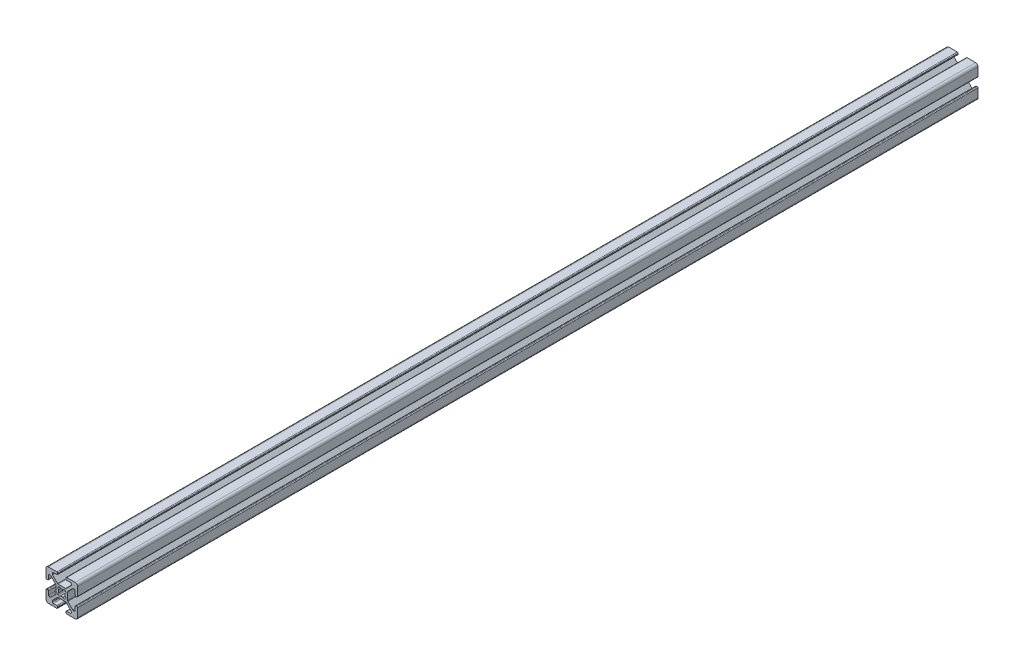
SolidWorks part; units mm, degrees
ref_plane "Front Plane" through (0, 0, 0) normal (0, 0, 1) x (1, 0, 0)
ref_plane "Top Plane" through (0, 0, 0) normal (0, 1, 0) x (1, 0, 0)
ref_plane "Right Plane" through (0, 0, 0) normal (1, 0, 0) x (0, 0, -1)
sketch "Sketch1" plane through (0, 0, 0) normal (0, 0, 1) x (1, 0, 0)
  line L0 (-5.0323, -0.3411) -> (-5.5163, -0.3411)
  line L1 (-6.0243, 0.1669) -> (-6.0243, 2.5159)
  line L2 (-4.5243, 0.1669) -> (-4.5243, 5.5289)
  line L3 (-10.8693, -5.355) -> (-10.8693, -0.5871)
  line L4 (-7.2582, 3.0239) -> (-6.5323, 3.0239)
  line L5 (-7.6174, 2.8752) -> (-10.7205, -0.2279)
  line L6 (-5.0323, -5.6011) -> (-5.5163, -5.6011)
  line L7 (-4.5243, -6.1091) -> (-4.5243, -11.4711)
  line L8 (-6.0243, -6.1091) -> (-6.0243, -8.4581)
  line L9 (-7.2582, -8.9661) -> (-6.5323, -8.9661)
  line L10 (-7.6174, -8.8173) -> (-10.7205, -5.7142)
  line L11 (-12.3994, -5.2756) -> (-12.2198, -5.096)
  line L12 (-17.1543, 6.5209) -> (-17.1543, 6.0369)
  line L13 (-17.6623, 7.0289) -> (-23.0243, 7.0289)
  line L14 (-17.6623, 5.5289) -> (-20.0113, 5.5289)
  line L15 (-12.1404, 0.6839) -> (-16.9082, 0.6839)
  line L16 (-20.5193, 4.295) -> (-20.5193, 5.0209)
  line L17 (-20.3705, 3.9358) -> (-17.2674, 0.8327)
  line L18 (-11.8943, 6.5209) -> (-11.8943, 6.0369)
  line L19 (-11.3863, 7.0289) -> (-6.0243, 7.0289)
  line L20 (-11.3863, 5.5289) -> (-9.0373, 5.5289)
  line L21 (-8.5293, 4.295) -> (-8.5293, 5.0209)
  line L22 (-8.6781, 3.9358) -> (-11.7812, 0.8327)
  line L23 (-12.2198, -0.8462) -> (-12.3994, -0.6666)
  line L24 (-24.0163, -5.6011) -> (-23.5323, -5.6011)
  line L25 (-24.5243, -6.1091) -> (-24.5243, -11.4711)
  line L26 (-23.0243, -6.1091) -> (-23.0243, -8.4581)
  line L27 (-18.1793, -0.5871) -> (-18.1793, -5.355)
  line L28 (-21.7904, -8.9661) -> (-22.5163, -8.9661)
  line L29 (-21.4312, -8.8173) -> (-18.3281, -5.7142)
  line L30 (-24.0163, -0.3411) -> (-23.5323, -0.3411)
  line L31 (-24.5243, 0.1669) -> (-24.5243, 5.5289)
  line L32 (-23.0243, 0.1669) -> (-23.0243, 2.5159)
  line L33 (-21.7904, 3.0239) -> (-22.5163, 3.0239)
  line L34 (-21.4312, 2.8752) -> (-18.3281, -0.2279)
  line L35 (-16.6492, -0.6666) -> (-16.8288, -0.8462)
  line L36 (-11.8943, -12.4631) -> (-11.8943, -11.9791)
  line L37 (-11.3863, -12.9711) -> (-6.0243, -12.9711)
  line L38 (-11.3863, -11.4711) -> (-9.0373, -11.4711)
  line L39 (-16.9082, -6.6261) -> (-12.1404, -6.6261)
  line L40 (-8.5293, -10.2371) -> (-8.5293, -10.9631)
  line L41 (-8.6781, -9.8779) -> (-11.7812, -6.7748)
  line L42 (-17.1543, -12.4631) -> (-17.1543, -11.9791)
  line L43 (-17.6623, -12.9711) -> (-23.0243, -12.9711)
  line L44 (-17.6623, -11.4711) -> (-20.0113, -11.4711)
  line L45 (-20.5193, -10.2371) -> (-20.5193, -10.9631)
  line L46 (-20.3705, -9.8779) -> (-17.2674, -6.7748)
  line L47 (-16.8288, -5.096) -> (-16.6492, -5.2756)
  arc A0 (-15.3283, -4.9062) -> (-13.7203, -4.9062) centre (-14.5243, -2.9711) ccw
  arc A1 (-6.0243, 2.5159) -> (-6.5323, 3.0239) centre (-6.5323, 2.5159) ccw
  arc A2 (-7.2582, 3.0239) -> (-7.6174, 2.8752) centre (-7.2582, 2.5159) ccw
  arc A3 (-10.7205, -0.2279) -> (-10.8693, -0.5871) centre (-10.3613, -0.5871) ccw
  arc A4 (-10.8693, -5.355) -> (-10.7205, -5.7142) centre (-10.3613, -5.355) ccw
  arc A5 (-7.6174, -8.8173) -> (-7.2582, -8.9661) centre (-7.2582, -8.4581) ccw
  arc A6 (-6.5323, -8.9661) -> (-6.0243, -8.4581) centre (-6.5323, -8.4581) ccw
  arc A7 (-5.5163, -5.6011) -> (-6.0243, -6.1091) centre (-5.5163, -6.1091) ccw
  arc A8 (-4.5243, -6.1091) -> (-5.0323, -5.6011) centre (-5.0323, -6.1091) ccw
  arc A9 (-5.0323, -0.3411) -> (-4.5243, 0.1669) centre (-5.0323, 0.1669) ccw
  arc A10 (-6.0243, 0.1669) -> (-5.5163, -0.3411) centre (-5.5163, 0.1669) ccw
  arc A11 (-13.7203, -4.9062) -> (-12.3994, -5.2756) centre (-12.9559, -4.7191) ccw
  arc A12 (-12.2198, -5.096) -> (-12.5892, -3.775) centre (-12.7763, -4.5395) ccw
  arc A13 (-17.1543, 6.5209) -> (-17.6623, 7.0289) centre (-17.6623, 6.5209) ccw
  arc A14 (-17.6623, 5.5289) -> (-17.1543, 6.0369) centre (-17.6623, 6.0369) ccw
  arc A15 (-12.5892, -3.775) -> (-12.5892, -2.1671) centre (-14.5243, -2.9711) ccw
  arc A16 (-17.2674, 0.8327) -> (-16.9082, 0.6839) centre (-16.9082, 1.1919) ccw
  arc A17 (-20.0113, 5.5289) -> (-20.5193, 5.0209) centre (-20.0113, 5.0209) ccw
  arc A18 (-20.5193, 4.295) -> (-20.3705, 3.9358) centre (-20.0113, 4.295) ccw
  arc A19 (-11.8943, 6.0369) -> (-11.3863, 5.5289) centre (-11.3863, 6.0369) ccw
  arc A20 (-11.3863, 7.0289) -> (-11.8943, 6.5209) centre (-11.3863, 6.5209) ccw
  arc A21 (-8.5293, 5.0209) -> (-9.0373, 5.5289) centre (-9.0373, 5.0209) ccw
  arc A22 (-8.6781, 3.9358) -> (-8.5293, 4.295) centre (-9.0373, 4.295) ccw
  arc A23 (-12.1404, 0.6839) -> (-11.7812, 0.8327) centre (-12.1404, 1.1919) ccw
  arc A24 (-12.5892, -2.1671) -> (-12.2198, -0.8462) centre (-12.7763, -1.4027) ccw
  arc A25 (-12.3994, -0.6666) -> (-13.7203, -1.0359) centre (-12.9559, -1.223) ccw
  arc A26 (-24.0163, -5.6011) -> (-24.5243, -6.1091) centre (-24.0163, -6.1091) ccw
  arc A27 (-23.0243, -6.1091) -> (-23.5323, -5.6011) centre (-23.5323, -6.1091) ccw
  arc A28 (-13.7203, -1.0359) -> (-15.3283, -1.0359) centre (-14.5243, -2.9711) ccw
  arc A29 (-18.3281, -5.7142) -> (-18.1793, -5.355) centre (-18.6873, -5.355) ccw
  arc A30 (-23.0243, -8.4581) -> (-22.5163, -8.9661) centre (-22.5163, -8.4581) ccw
  arc A31 (-21.7904, -8.9661) -> (-21.4312, -8.8173) centre (-21.7904, -8.4581) ccw
  arc A32 (-23.5323, -0.3411) -> (-23.0243, 0.1669) centre (-23.5323, 0.1669) ccw
  arc A33 (-24.5243, 0.1669) -> (-24.0163, -0.3411) centre (-24.0163, 0.1669) ccw
  arc A34 (-22.5163, 3.0239) -> (-23.0243, 2.5159) centre (-22.5163, 2.5159) ccw
  arc A35 (-21.4312, 2.8752) -> (-21.7904, 3.0239) centre (-21.7904, 2.5159) ccw
  arc A36 (-18.1793, -0.5871) -> (-18.3281, -0.2279) centre (-18.6873, -0.5871) ccw
  arc A37 (-15.3283, -1.0359) -> (-16.6492, -0.6666) centre (-16.0927, -1.223) ccw
  arc A38 (-16.8288, -0.8462) -> (-16.4594, -2.1671) centre (-16.2723, -1.4027) ccw
  arc A39 (-11.8943, -12.4631) -> (-11.3863, -12.9711) centre (-11.3863, -12.4631) ccw
  arc A40 (-11.3863, -11.4711) -> (-11.8943, -11.9791) centre (-11.3863, -11.9791) ccw
  arc A41 (-16.4594, -2.1671) -> (-16.4594, -3.775) centre (-14.5243, -2.9711) ccw
  arc A42 (-11.7812, -6.7748) -> (-12.1404, -6.6261) centre (-12.1404, -7.1341) ccw
  arc A43 (-9.0373, -11.4711) -> (-8.5293, -10.9631) centre (-9.0373, -10.9631) ccw
  arc A44 (-8.5293, -10.2371) -> (-8.6781, -9.8779) centre (-9.0373, -10.2371) ccw
  arc A45 (-17.1543, -11.9791) -> (-17.6623, -11.4711) centre (-17.6623, -11.9791) ccw
  arc A46 (-17.6623, -12.9711) -> (-17.1543, -12.4631) centre (-17.6623, -12.4631) ccw
  arc A47 (-20.5193, -10.9631) -> (-20.0113, -11.4711) centre (-20.0113, -10.9631) ccw
  arc A48 (-20.3705, -9.8779) -> (-20.5193, -10.2371) centre (-20.0113, -10.2371) ccw
  arc A49 (-16.9082, -6.6261) -> (-17.2674, -6.7748) centre (-16.9082, -7.1341) ccw
  arc A50 (-16.4594, -3.775) -> (-16.8288, -5.096) centre (-16.2723, -4.5395) ccw
  arc A51 (-16.6492, -5.2756) -> (-15.3283, -4.9062) centre (-16.0927, -4.7191) ccw
  arc A52 (-4.5243, 5.5289) -> (-6.0243, 7.0289) centre (-6.0243, 5.5289) ccw
  arc A53 (-6.0243, -12.9711) -> (-4.5243, -11.4711) centre (-6.0243, -11.4711) ccw
  arc A54 (-24.5243, -11.4711) -> (-23.0243, -12.9711) centre (-23.0243, -11.4711) ccw
  arc A55 (-23.0243, 7.0289) -> (-24.5243, 5.5289) centre (-23.0243, 5.5289) ccw
extrude "Extrude1" add sketch "Sketch1" along normal blind 570
